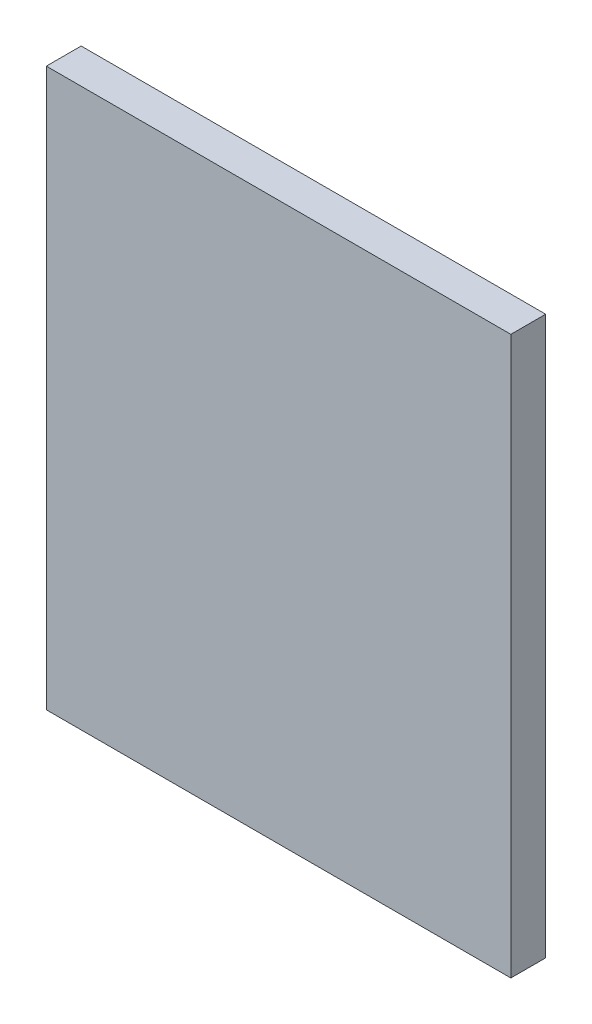
SolidWorks part; units mm, degrees
ref_plane "Front Plane" through (0, 0, 0) normal (0, 0, 1) x (1, 0, 0)
ref_plane "Top Plane" through (0, 0, 0) normal (0, 1, 0) x (1, 0, 0)
ref_plane "Right Plane" through (0, 0, 0) normal (1, 0, 0) x (0, 0, -1)
sketch "Sketch1" plane through (0, 0, 0) normal (0, 0, 1) x (1, 0, 0)
  line L1 (0, 0) -> (127, 0)
  line L2 (0, 0) -> (0, 152.4)
  line L3 (0, 152.4) -> (127, 152.4)
  line L4 (127, 0) -> (127, 152.4)
  dimension "D1" = 152.4
  dimension "D2" = 127
extrude "Boss-Extrude1" add sketch "Sketch1" along normal blind 9.525
sketch "Sketch2" plane through (0, 0, 0) normal (0, 0, 1) x (1, 0, 0)
  line L0 (63.5, 152.4) -> (63.5, 0)
  line L1 (127, 152.4) -> (0, 152.4) construction
  line L2 (0, 0) -> (127, 0) construction
